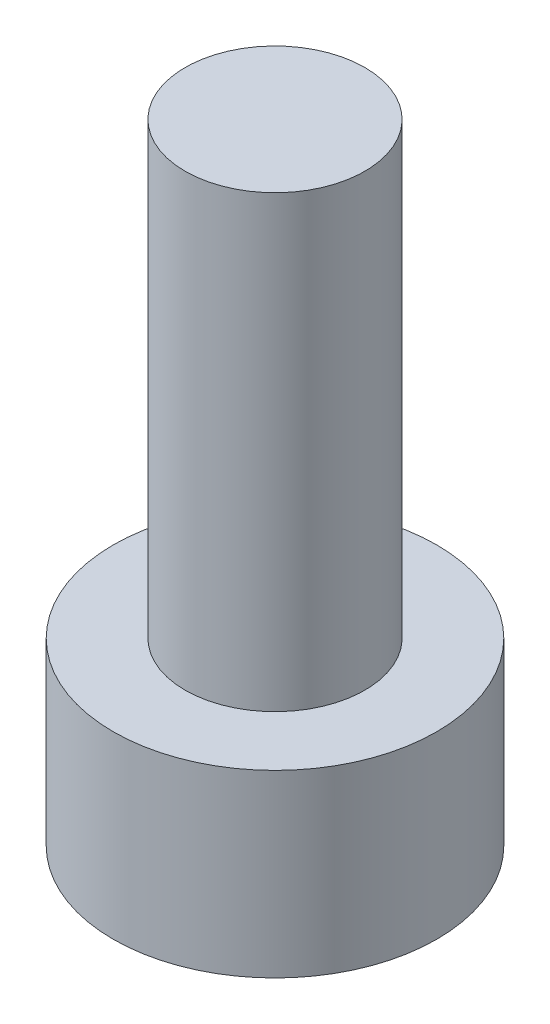
SolidWorks part; units mm, degrees
material "Brass"
ref_plane "Front Plane" through (0, 0, 0) normal (0, 0, 1) x (1, 0, 0)
ref_plane "Top Plane" through (0, 0, 0) normal (0, 1, 0) x (1, 0, 0)
ref_plane "Right Plane" through (0, 0, 0) normal (1, 0, 0) x (0, 0, -1)
sketch "Sketch1" plane through (0, 0, 0) normal (0, 1, 0) x (1, 0, 0)
  circle A0 centre (0, 0) radius 1.27
  dimension "D1" = 2.54
extrude "Boss-Extrude1" add sketch "Sketch1" along normal blind 6.35
sketch "Sketch2" plane through (0, 0, 0) normal (0, -1, 0) x (1, 0, 0)
  circle A0 centre (0, 0) radius 2.286
extrude "Boss-Extrude2" add sketch "Sketch2" along normal blind 2.54
sketch "Sketch3" plane through (0, -2.54, 0) normal (0, -1, 0) x (-1, 0, 0)
  line L1 (-0.068, 1.8502) -> (-1.6364, 0.8662)
  line L2 (-1.6364, 0.8662) -> (-1.5683, -0.984)
  line L3 (-1.5683, -0.984) -> (0.068, -1.8502)
  line L4 (0.068, -1.8502) -> (1.6364, -0.8662)
  line L5 (1.6364, -0.8662) -> (1.5683, 0.984)
  line L6 (1.5683, 0.984) -> (-0.068, 1.8502)
  circle A0 centre (0, 0) radius 1.6034 construction
extrude "Cut-Extrude1" cut sketch "Sketch3" against normal blind 1.778
